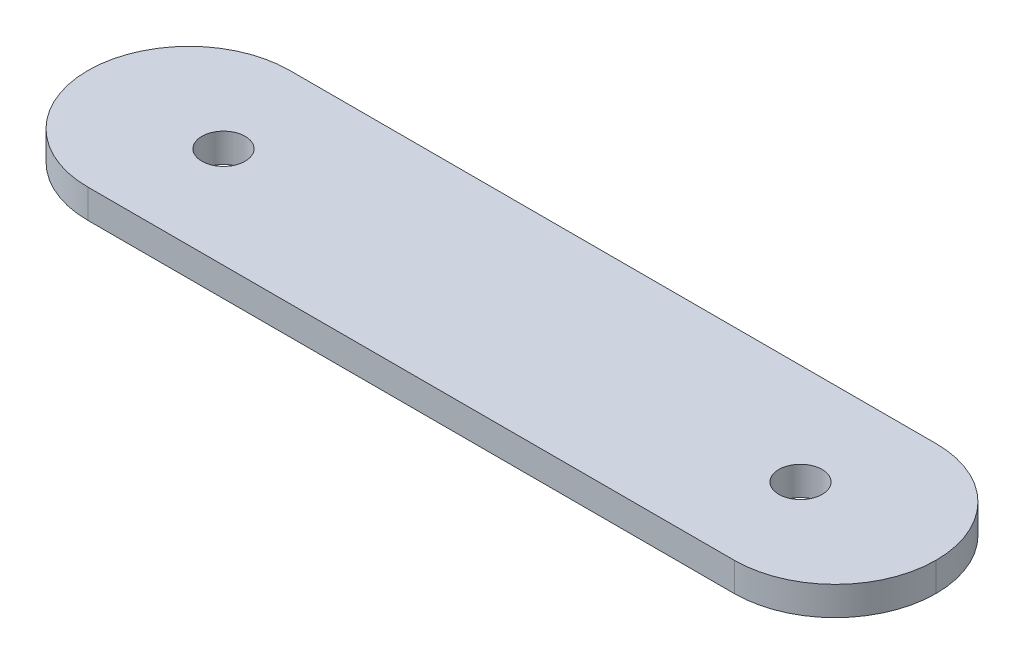
SolidWorks part; units mm, degrees
material "Tin Bearing Bronze"
ref_plane "Front Plane" through (0, 0, 0) normal (0, 0, 1) x (1, 0, 0)
ref_plane "Top Plane" through (0, 0, 0) normal (0, 1, 0) x (1, 0, 0)
ref_plane "Right Plane" through (0, 0, 0) normal (1, 0, 0) x (0, 0, -1)
sketch "Sketch1" plane through (0, 0, 0) normal (0, 1, 0) x (1, 0, 0)
  line L0 (93.6708, 4.0264) -> (-33.3292, 4.0264) construction
  line L1 (101.3162, 26.2514) -> (101.3162, -18.1986) construction
  line L2 (-40.9746, 26.2514) -> (-40.9746, -18.1986) construction
  line L3 (123.5158, 4.001) -> (-63.1742, 4.001) construction
  line L6 (-40.9746, -18.1986) -> (101.3162, -18.1986)
  line L7 (-63.1742, 4.001) -> (-63.1742, 4.0518)
  line L8 (-40.9746, 26.2514) -> (101.3162, 26.2514)
  line L9 (123.5158, 4.001) -> (123.5158, 4.0518)
  circle A0 centre (-33.3292, 4.0264) radius 4.7625
  circle A1 centre (93.6708, 4.0264) radius 4.7625
  arc A2 (101.3162, -18.1986) -> (123.5158, 4.001) centre (101.3162, 4.001) ccw
  arc A3 (101.3162, 26.2514) -> (123.5158, 4.0518) centre (101.3162, 4.0518) cw
  arc A4 (-63.1742, 4.0518) -> (-40.9746, 26.2514) centre (-40.9746, 4.0518) cw
  arc A5 (-40.9746, -18.1986) -> (-63.1742, 4.001) centre (-40.9746, 4.001) cw
  point P4 (0, 0)
  point P7 (0, 0)
  point P10 (93.6708, 4.0264)
  dimension "D1" = 9.525
  dimension "D2" = 9.525
  dimension "D3" = 22.1996
  dimension "D4" = 127
  dimension "D5" = 186.69
  dimension "D6" = 44.45
extrude "Boss-Extrude1" add sketch "Sketch1" along normal blind 6.35
